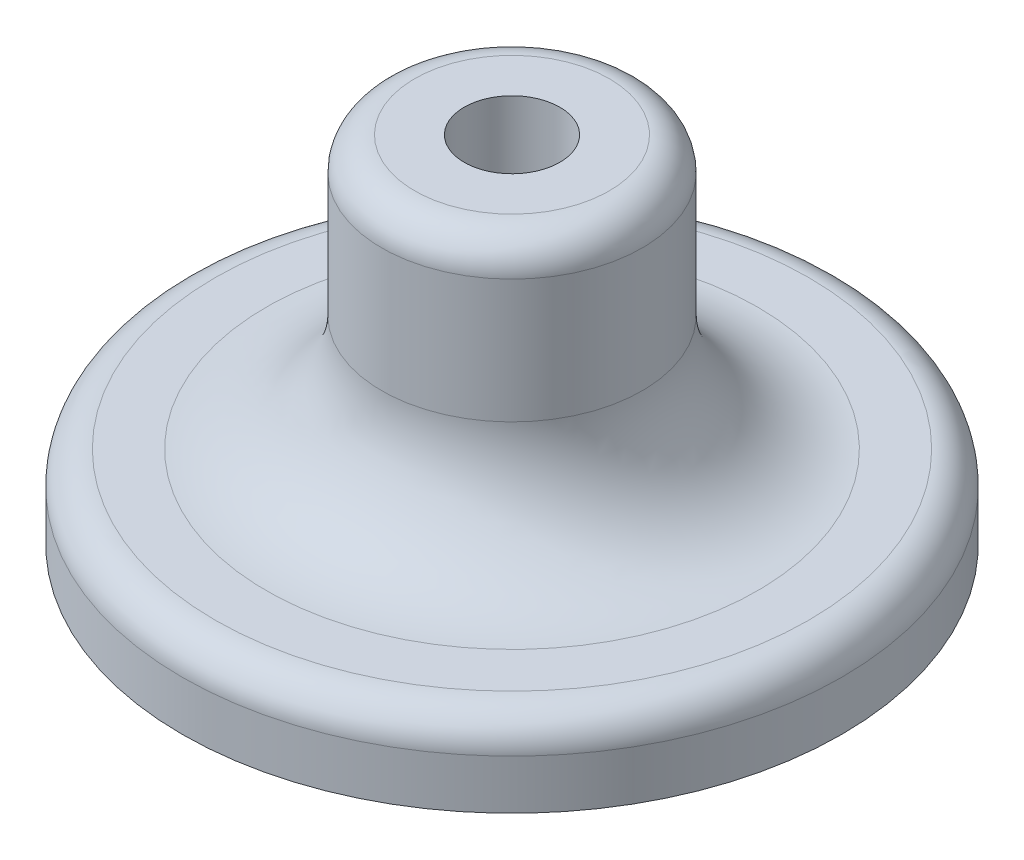
SolidWorks part; units mm, degrees
ref_plane "Front Plane" through (0, 0, 0) normal (0, 0, 1) x (1, 0, 0)
ref_plane "Top Plane" through (0, 0, 0) normal (0, 1, 0) x (1, 0, 0)
ref_plane "Right Plane" through (0, 0, 0) normal (1, 0, 0) x (0, 0, -1)
sketch "Sketch2" plane through (0, 0, 0) normal (1, 0, 0) x (0, 0, -1)
  line L0 (0, 0) -> (-20, 0)
  line L1 (-20, 0) -> (-20, 3)
  line L2 (0, 0) -> (0, 1.5)
  line L3 (0, 1.5) -> (-2.9, 1.5)
  line L4 (-2.9, 1.5) -> (-2.9, 21.5)
  line L5 (-2.9, 21.5) -> (-5.9, 21.5)
  line L7 (-7.9, 19.5) -> (-7.9, 12)
  line L8 (-14.9, 5) -> (-18, 5)
  arc A0 (-18, 5) -> (-20, 3) centre (-18, 3) ccw
  arc A1 (-7.9, 12) -> (-14.9, 5) centre (-14.9, 12) cw
  arc A2 (-5.9, 21.5) -> (-7.9, 19.5) centre (-5.9, 19.5) ccw
  point P11 (-20, 5)
  point P16 (-7.9, 21.5)
  dimension "D7" = 2
  dimension "D8" = 7
  dimension "D9" = 2
  dimension "D1" = 2.9
  dimension "D2" = 1.5
  dimension "D3" = 20
  dimension "D4" = 5
  dimension "D5" = 20
  dimension "D6" = 5
revolve "Revolve1" add sketch "Sketch2" angle 360 about L2
